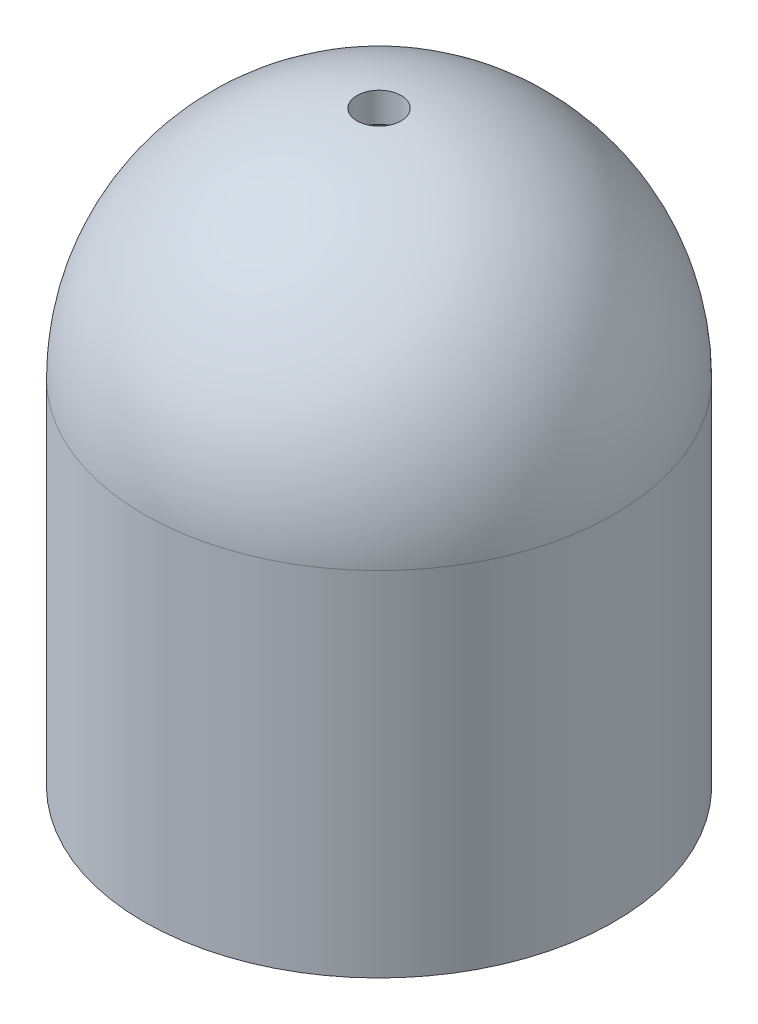
SolidWorks part; units mm, degrees
ref_plane "Front Plane" through (0, 0, 0) normal (0, 0, 1) x (1, 0, 0)
ref_plane "Top Plane" through (0, 0, 0) normal (0, 1, 0) x (1, 0, 0)
ref_plane "Right Plane" through (0, 0, 0) normal (1, 0, 0) x (0, 0, -1)
sketch "Sketch1" plane through (0, 0, 0) normal (0, 0, 1) x (1, 0, 0)
  line L0 (44.45, 50.8) -> (44.45, 44.45)
  line L2 (0, 0) -> (0, -76.2)
  line L3 (0, -76.2) -> (-6.35, -76.2)
  line L4 (-6.35, 0) -> (-6.35, -76.2)
  arc A0 (-6.35, 0) -> (44.45, 50.8) centre (44.45, 0) cw
  arc A1 (0, 0) -> (44.45, 44.45) centre (44.45, 0) cw
  point P5 (0, 0)
  point P8 (0, 0)
  point P11 (0, 0)
  point P12 (0, 0)
  dimension "D6" = 76.2
  dimension "D1" = 76.2
  dimension "D2" = 6.35
  dimension "D3" = 44.45
  dimension "D5" = 6.35
revolve "Revolve1" add sketch "Sketch1" angle 360 about L0
sketch "Sketch2" plane through (0, 0, 0) normal (0, 1, 0) x (1, 0, 0)
  circle A0 centre (44.45, 0) radius 4.7625
  dimension "D1" = 9.525
  dimension "D2" = 44.45
extrude "Cut-Extrude2" cut sketch "Sketch2" along normal blind 54.61 contours A0
